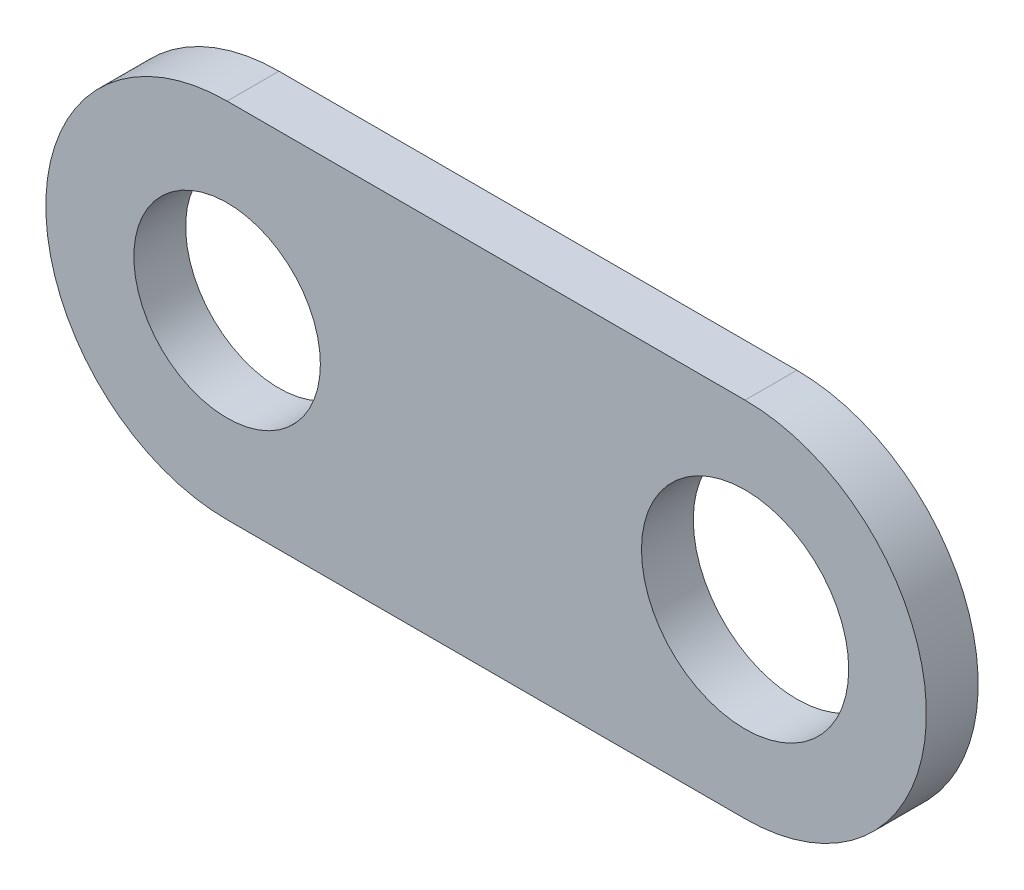
SolidWorks part; units mm, degrees
ref_plane "Front Plane" through (0, 0, 0) normal (0, 0, 1) x (1, 0, 0)
ref_plane "Top Plane" through (0, 0, 0) normal (0, 1, 0) x (1, 0, 0)
ref_plane "Right Plane" through (0, 0, 0) normal (1, 0, 0) x (0, 0, -1)
sketch "Sketch1" plane through (0, 0, 0) normal (0, 0, 1) x (1, 0, 0)
  line L0 (0, 0) -> (63.5, 0) construction
  line L1 (0, 22.225) -> (63.5, 22.225)
  line L2 (0, -22.225) -> (63.5, -22.225)
  arc A0 (0, 22.225) -> (0, -22.225) centre (0, 0) ccw
  arc A1 (63.5, -22.225) -> (63.5, 22.225) centre (63.5, 0) ccw
  point P3 (31.75, 0)
  point P8 (0, 0)
  dimension "D1" = 63.5
  dimension "D2" = 44.45
extrude "Link-Body" add sketch "Sketch1" along normal blind 6.35
sketch "Sketch2" plane through (0, 0, 6.35) normal (0, 0, 1) x (1, 0, 0)
  circle A0 centre (0, 0) radius 11.4332
  circle A1 centre (63.5, 0) radius 12.7032
  dimension "D1" = 22.8664
  dimension "D2" = 25.4063
extrude "Cut-Extrude1" cut sketch "Sketch2" against normal through all
equation "\"Link_width\"= 1.750in"
equation "\"Link_thickness\"= 0.250in"
equation "\"Hole_spacing\"= 2.500in"
equation "\"Pin_basic\"= 0.900in"
equation "\"Bracket_pin_hole\"= \"Pin_basic\" + 0.00025in"
equation "\"Shaft_hole\"= 1.00025in"
equation "\"D1@Sketch1\"=\"Hole_spacing\""
equation "\"D2@Sketch1\"=\"Link_width\""
equation "\"D1@Link-Body\" = \"Link_thickness\""
equation "\"D1@Sketch2\"=\"Bracket_pin_hole\""
equation "\"D2@Sketch2\"=\"Shaft_hole\""
